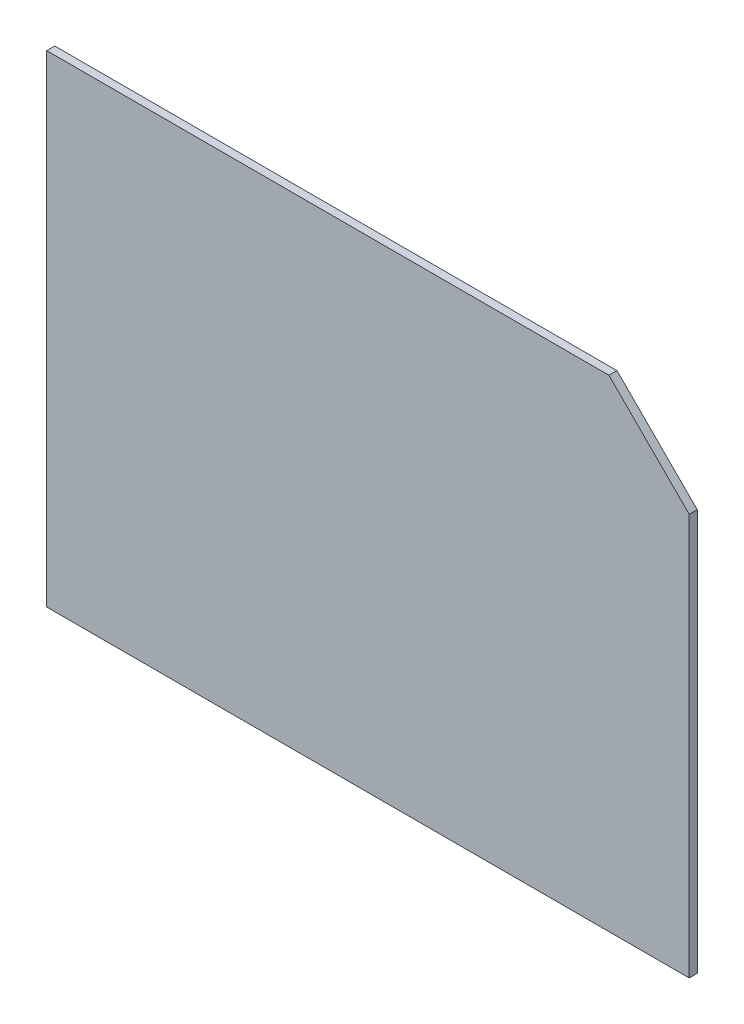
SolidWorks part; units mm, degrees
ref_plane "Front Plane" through (0, 0, 0) normal (0, 0, 1) x (1, 0, 0)
ref_plane "Top Plane" through (0, 0, 0) normal (0, 1, 0) x (1, 0, 0)
ref_plane "Right Plane" through (0, 0, 0) normal (1, 0, 0) x (0, 0, -1)
sketch "Sketch2" plane through (0, 0, 0) normal (0, 0, 1) x (1, 0, 0)
  line L1 (-1000, 750) -> (1000, 750)
  line L2 (-1000, 750) -> (-1000, -750)
  line L3 (-1000, -750) -> (1000, -750)
  line L4 (1000, 750) -> (1000, -750)
  dimension "wall_length" = 2000
  dimension "wall_height" = 1500
  dimension "D1" = 1000
  dimension "D2" = 750
extrude "Boss-Extrude1" add sketch "Sketch2" against normal blind 25
sketch "Sketch3" plane through (0, 0, 0) normal (0, 0, 1) x (1, 0, 0)
  line L5 (1000, 500) -> (1000, 750)
  line L6 (1000, -750) -> (1000, 750) construction
  line L7 (1000, 750) -> (750, 750)
  line L8 (1000, 750) -> (-1000, 750) construction
  line L9 (750, 750) -> (1000, 500)
  dimension "D1" = 250
  dimension "D2" = 45
extrude "Cut-Extrude1" cut sketch "Sketch3" against normal blind 932
equation "\"D1@Sketch2\"=\"wall_length@Sketch2\"/2"
equation "\"D2@Sketch2\"=\"wall_height@Sketch2\"/2"
